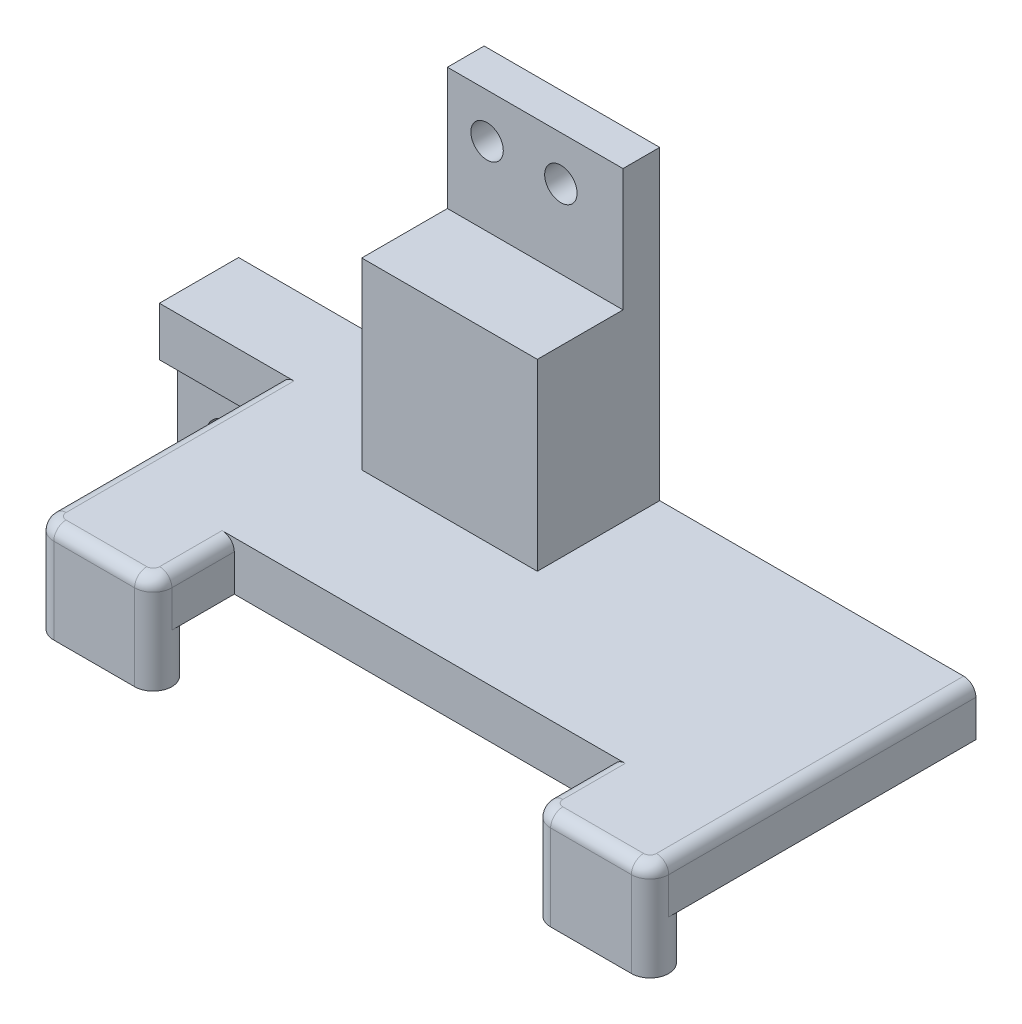
SolidWorks part; units mm, degrees
ref_plane "Front" through (0, 0, 0) normal (0, 0, 1) x (1, 0, 0)
ref_plane "Top" through (0, 0, 0) normal (0, 1, 0) x (1, 0, 0)
ref_plane "Right" through (0, 0, 0) normal (1, 0, 0) x (0, 0, -1)
sketch "Sketch1" plane through (0, 0, 0) normal (0, 1, 0) x (1, 0, 0)
  line L0 (0, -55) -> (0, 55) construction
  line L5 (-23.6, 10.5423) -> (-17, 10.5423)
  line L6 (-23.6, 7.4923) -> (-17, 7.4923)
  line L7 (23.6, 7.4923) -> (17, 7.4923)
  line L8 (23.6, 10.5423) -> (17, 10.5423)
  arc A0 (-23.6, 10.5423) -> (-23.6, 7.4923) centre (-23.6, 9.0173) ccw
  arc A1 (-17, 7.4923) -> (-17, 10.5423) centre (-17, 9.0173) ccw
  arc A2 (23.6, 10.5423) -> (23.6, 7.4923) centre (23.6, 9.0173) cw
  arc A3 (17, 7.4923) -> (17, 10.5423) centre (17, 9.0173) cw
  dimension "D1" = 3.05
  dimension "D2" = 6.6
  dimension "D3" = 17
extrude "Boss-Extrude1" add sketch "Sketch1" along normal blind 4
sketch "Sketch3" plane through (0, 4, 0) normal (0, 1, 0) x (1, 0, 0)
  line L1 (17, 7.4923) -> (23.6, 7.4923) construction
  line L2 (-23.6, 7.4923) -> (-17, 7.4923) construction
  line L3 (-35.125, 34.1173) -> (25.125, 34.1173)
  line L5 (17, 7.4923) -> (23.6, 7.4923)
  line L6 (-23.6, 7.4923) -> (-17, 7.4923)
  line L8 (-25.125, 9.0173) -> (-25.125, 18.7234)
  line L9 (-15.475, 14.1173) -> (15.475, 14.1173)
  line L11 (-25.125, 34.1173) -> (25.125, 34.1173)
  line L13 (-15.475, 9.0173) -> (-15.475, 14.1173)
  line L14 (0, -1.6775) -> (0, 1.6775) construction
  line L15 (23.6, 7.4923) -> (17, 7.4923)
  line L16 (15.475, 9.0173) -> (15.475, 14.1173)
  line L17 (15.475, 14.1173) -> (-15.475, 14.1173)
  line L18 (-25.125, 18.7234) -> (-25.125, 34.1173)
  line L19 (25.125, 34.1173) -> (25.125, 18.7234)
  line L20 (25.125, 9.0173) -> (25.125, 18.7234)
  line L21 (-35.125, 34.1173) -> (-35.125, 27.6439)
  line L22 (-35.125, 27.6439) -> (25.125, 27.6439)
  line L23 (25.125, 34.1173) -> (25.125, 27.6439)
  arc A0 (23.6, 7.4923) -> (23.6, 10.5423) centre (23.6, 9.0173) ccw construction
  arc A1 (17, 10.5423) -> (17, 7.4923) centre (17, 9.0173) ccw construction
  arc A2 (-23.6, 10.5423) -> (-23.6, 7.4923) centre (-23.6, 9.0173) ccw construction
  arc A3 (-17, 7.4923) -> (-17, 10.5423) centre (-17, 9.0173) ccw construction
  arc A4 (23.6, 7.4923) -> (25.125, 9.0173) centre (23.6, 9.0173) ccw
  arc A5 (15.475, 9.0173) -> (17, 7.4923) centre (17, 9.0173) ccw
  arc A6 (-25.125, 9.0173) -> (-23.6, 7.4923) centre (-23.6, 9.0173) ccw
  arc A7 (-17, 7.4923) -> (-15.475, 9.0173) centre (-17, 9.0173) ccw
  arc A8 (25.125, 9.0173) -> (23.6, 7.4923) centre (23.6, 9.0173) cw
  arc A9 (17, 7.4923) -> (15.475, 9.0173) centre (17, 9.0173) cw
  arc M5 (-23.6, 10.5423) -> (-23.6, 7.4923) centre (-23.6, 9.0173) ccw
  line M6 (-23.6, 7.4923) -> (-17, 7.4923)
  arc M7 (-17, 7.4923) -> (-17, 10.5423) centre (-17, 9.0173) ccw
  line M8 (-17, 10.5423) -> (-23.6, 10.5423)
  dimension "D1" = 5.1
  dimension "D2" = 20
  dimension "D3" = 10
extrude "Boss-Extrude3" add sketch "Sketch3" along normal blind 4 contours L16 A5 L5 A4 L20 L19 L11 L18 L8 L13 L9 M5 M8 M7 | M8 M5 M6 M7 | L21 L22 L18 L3 | L23 L3 L19 L22 | L18 L22 L19 L3
fillet "Fillet2" radius 1 10 edges at (-25.125, 8, -18.3306) (-24.6783, 8, -7.9389) (-15.475, 8, -11.5673) (-15.9217, 8, -7.9389) (15.475, 8, -11.5673) (15.9217, 8, -7.9389) (25.125, 8, -21.5673) (24.6783, 8, -7.9389) (-20.3, 8, -7.4923) (20.3, 8, -7.4923)
sketch "Sketch4" plane through (0, 8, 0) normal (0, 1, 0) x (1, 0, 0)
  line L0 (-35.125, 34.1173) -> (24.125, 34.1173) construction
  line L1 (-15.0591, 34.1173) -> (-0.7115, 34.1173)
  line L2 (-15.0591, 34.1173) -> (-15.0591, 24.1173)
  line L3 (-15.0591, 24.1173) -> (-0.7115, 24.1173)
  line L4 (-0.7115, 34.1173) -> (-0.7115, 24.1173)
  dimension "D1" = 10
extrude "Boss-Extrude4" add sketch "Sketch4" along normal blind 15
sketch "Sketch6" plane through (0, 23, 0) normal (0, 1, 0) x (1, 0, 0)
  line L0 (-0.7115, 24.1173) -> (-0.7115, 34.1173) construction
  line L1 (-15.0591, 34.1173) -> (-0.7115, 34.1173)
  line L2 (-15.0591, 34.1173) -> (-15.0591, 31.1173)
  line L3 (-15.0591, 31.1173) -> (-0.7115, 31.1173)
  line L4 (-0.7115, 34.1173) -> (-0.7115, 31.1173)
  dimension "D1" = 3
extrude "Boss-Extrude6" add sketch "Sketch6" along normal blind 10
sketch "Sketch7" plane through (0, 0, -31.1173) normal (0, 0, 1) x (1, 0, 0)
  line L0 (-15.0591, 23) -> (-0.7115, 23) construction
  line L1 (-15.0591, 33) -> (-15.0591, 23) construction
  circle A0 centre (-11.8191, 29.375) radius 1.325
  circle A1 centre (-5.7891, 29.375) radius 1.325
  dimension "D1" = 2.65
  dimension "D2" = 6.375
  dimension "D3" = 3.24
  dimension "D4" = 6.03
extrude "Cut-Extrude1" cut sketch "Sketch7" against normal up to next
sketch "Sketch8" plane through (0, 0, -34.1173) normal (0, 0, -1) x (-1, 0, 0)
  line L1 (35.125, 8) -> (18.667, 8)
  line L2 (35.125, 8) -> (35.125, -7.1349)
  line L3 (35.125, -7.1349) -> (18.667, -7.1349)
  line L4 (18.667, 8) -> (18.667, -7.1349)
  line L12 (35.125, 4) -> (35.125, 8)
  line L13 (35.125, 8) -> (15.0591, 8)
  line L14 (15.0591, 8) -> (15.0591, 33)
  line L15 (15.0591, 33) -> (0.7115, 33)
  line L16 (0.7115, 33) -> (0.7115, 8)
  line L17 (0.7115, 8) -> (-24.125, 8)
  line L18 (35.125, 4) -> (35.125, 8)
  line L19 (-25.125, 4) -> (35.125, 4)
  line L21 (35.125, 8) -> (15.0591, 8)
  line L22 (15.0591, 8) -> (15.0591, 33)
  line L23 (15.0591, 33) -> (0.7115, 33)
  line L24 (0.7115, 33) -> (0.7115, 8)
  line L25 (0.7115, 8) -> (-24.125, 8)
  line L27 (-25.125, 4) -> (35.125, 4)
  line L28 (-25.125, 7) -> (-25.125, 4)
  line L30 (-25.125, 7) -> (-25.125, 4)
  circle A0 centre (22.9848, -0.8312) radius 1.8
  circle A1 centre (30.9848, -0.8312) radius 1.8
  arc A3 (-24.125, 8) -> (-25.125, 7) centre (-24.125, 7) ccw
  arc A4 (-24.125, 8) -> (-25.125, 7) centre (-24.125, 7) ccw
  point P10 (27.6487, -2.7709)
  point P11 (15.0591, -2.8318)
  point P12 (18.7848, -1.3018)
  point P14 (27.6553, -1.2922)
  point P16 (14.663, -2.8282)
  point P18 (30.3689, -1.0622)
  point P20 (30.9848, -0.8312)
  dimension "D1" = 3.6
  dimension "D2" = 8
  dimension "D3" = 0
extrude "Boss-Extrude7" add sketch "Sketch8" against normal blind 5
